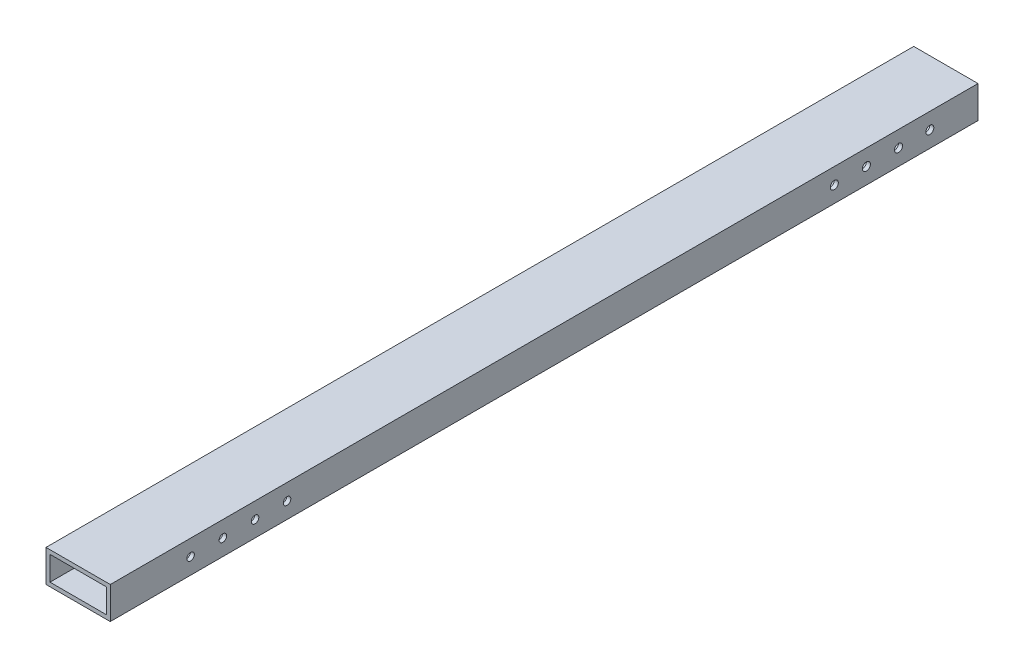
SolidWorks part; units mm, degrees
ref_plane "Front Plane" through (0, 0, 0) normal (0, 0, 1) x (1, 0, 0)
ref_plane "Top Plane" through (0, 0, 0) normal (0, 1, 0) x (1, 0, 0)
ref_plane "Right Plane" through (0, 0, 0) normal (1, 0, 0) x (0, 0, -1)
sketch "Sketch1" plane through (0, 0, 0) normal (0, 0, 1) x (1, 0, 0)
  line L0 (-22.225, 9.525) -> (22.225, 9.525)
  line L2 (-25.4, 12.7) -> (25.4, 12.7)
  line L3 (-25.4, 12.7) -> (-25.4, -12.7)
  line L4 (-25.4, -12.7) -> (25.4, -12.7)
  line L5 (25.4, 12.7) -> (25.4, -12.7)
  line L10 (22.225, 9.525) -> (22.225, -9.525)
  line L11 (-22.225, -9.525) -> (22.225, -9.525)
  line L12 (-22.225, 9.525) -> (-22.225, -9.525)
  point P12 (0, 12.7)
  point P14 (25.4, 0)
  dimension "Wall Thickness" = 3.175
  dimension "Outside Width" = 50.8
  dimension "Outside Height" = 25.4
  dimension "Inside Height" = 19.05
  dimension "Inside Width" = 44.45
sketch "Sketch2" plane through (0, 0, 0) normal (1, 0, 0) x (0, 0, -1)
  line L0 (342.9, 0) -> (-342.9, 0)
  point P4 (0, 0)
  point P7 (-342.9, 0)
  point P10 (342.9, 0)
  dimension "Length" = 685.8
sketch "Sketch3" plane through (0, 0, 0) normal (0, 0, 1) x (1, 0, 0)
  line L21 (25.4, 12.7) -> (-25.4, 12.7)
  line L22 (25.4, -12.7) -> (25.4, 12.7)
  line L23 (-25.4, -12.7) -> (25.4, -12.7)
  line L24 (-25.4, 12.7) -> (-25.4, -12.7)
  line L25 (25.4, 12.7) -> (-25.4, 12.7)
  line L26 (25.4, -12.7) -> (25.4, 12.7)
  line L27 (-25.4, -12.7) -> (25.4, -12.7)
  line L28 (-25.4, 12.7) -> (-25.4, -12.7)
  line L29 (22.225, 9.525) -> (-22.225, 9.525)
  line L30 (22.225, -9.525) -> (22.225, 9.525)
  line L31 (-22.225, -9.525) -> (22.225, -9.525)
  line L32 (-22.225, 9.525) -> (-22.225, -9.525)
  line L33 (22.225, 9.525) -> (-22.225, 9.525)
  line L34 (22.225, -9.525) -> (22.225, 9.525)
  line L35 (-22.225, -9.525) -> (22.225, -9.525)
  line L36 (-22.225, 9.525) -> (-22.225, -9.525)
  dimension "D1" = 0
  dimension "D2" = 0
extrude "Boss-Extrude1" add sketch "Sketch3" along normal up to vertex (342.9 mm away) and the other way up to vertex (342.9 mm away) up to point (0, 0, 342.9) other way up to point (0, 0, -342.9)
sketch "Drawing Reference" plane through (0, 0, 0) normal (1, 0, 0) x (0, 0, -1)
  line L0 (-342.9, 0) -> (342.9, 0) construction
  line L1 (0, -12.7) -> (0, 12.7) construction
  line L2 (-342.9, -12.7) -> (342.9, -12.7) construction
  line L5 (-342.9, 12.7) -> (342.9, 12.7) construction
  point P7 (-306.324, 0)
  point P8 (306.324, 0)
  dimension "D1" = 36.576
sketch "Sketch5" plane through (25.4, 0, 0) normal (1, 0, 0) x (0, 0, -1)
  line L0 (-342.9, 0) -> (-279.4, 0)
  line L1 (-342.9, -12.7) -> (-342.9, 12.7) construction
  line L2 (-279.4, 0) -> (-253.9075, 0)
  line L3 (-253.9075, 0) -> (-228.4933, 0)
  line L4 (-228.4933, 0) -> (-203.1963, 0)
  point P5 (0, 0)
  point P10 (0, 0)
  point P11 (0, 0)
hole_wizard "A (0.234) Diameter Hole1" positions "Sketch6" profile "Sketch7" hole size "A" standard "ANSI Inch" end condition through all
sketch "Sketch6" plane through (25.4, 0, 0) normal (1, 0, 0) x (0, 0, -1)
  point P0 (-279.4, 0)
  point P3 (-253.9075, 0)
  point P6 (-228.4933, 0)
  point P9 (-203.1963, 0)
sketch "Sketch7" plane through (25.4, 0, 279.4) normal (0, 1, 0) x (0, 0, -1)
  line L0 (0, 0) -> (0, 50.8)
  line L1 (0, 50.8) -> (2.9718, 50.8)
  line L2 (2.9718, 50.8) -> (2.9718, 0)
  line L5 (2.9718, 0) -> (0, 0)
  line L11 (0, -6.35) -> (0, 107.95) construction
  dimension "Thru Hole Dia." = 5.9436
  dimension "Thru Hole Depth" = 50.8
sketch "Sketch8" plane through (25.4, 0, 0) normal (1, 0, 0) x (0, 0, -1)
  line L0 (342.9, 0) -> (304.8, 0)
  line L1 (342.9, -12.7) -> (342.9, 12.7) construction
  line L2 (304.8, 0) -> (280.1118, 0)
  line L3 (280.1118, 0) -> (254.7118, 0)
  line L4 (254.7118, 0) -> (229.3118, 0)
hole_wizard "1/4 (0.25) Diameter Hole2" positions "Sketch9" profile "Sketch11" hole size "1/4" standard "ANSI Inch" end condition through all
sketch "Sketch9" plane through (25.4, 0, 0) normal (1, 0, 0) x (0, 0, -1)
  point P0 (304.8, 0)
  point P3 (280.1118, 0)
  point P6 (254.7118, 0)
  point P9 (229.3118, 0)
sketch "Sketch11" plane through (25.4, 0, -304.8) normal (0, 1, 0) x (0, 0, -1)
  line L0 (0, 0) -> (0, 50.8)
  line L1 (0, 50.8) -> (3.175, 50.8)
  line L2 (3.175, 50.8) -> (3.175, 0)
  line L5 (3.175, 0) -> (0, 0)
  line L11 (0, -6.35) -> (0, 107.95) construction
  dimension "Thru Hole Dia." = 6.35
  dimension "Thru Hole Depth" = 50.8
equation "\"D1@Drawing Reference\"=\"Outside Width@Sketch1\" * 0.72"
